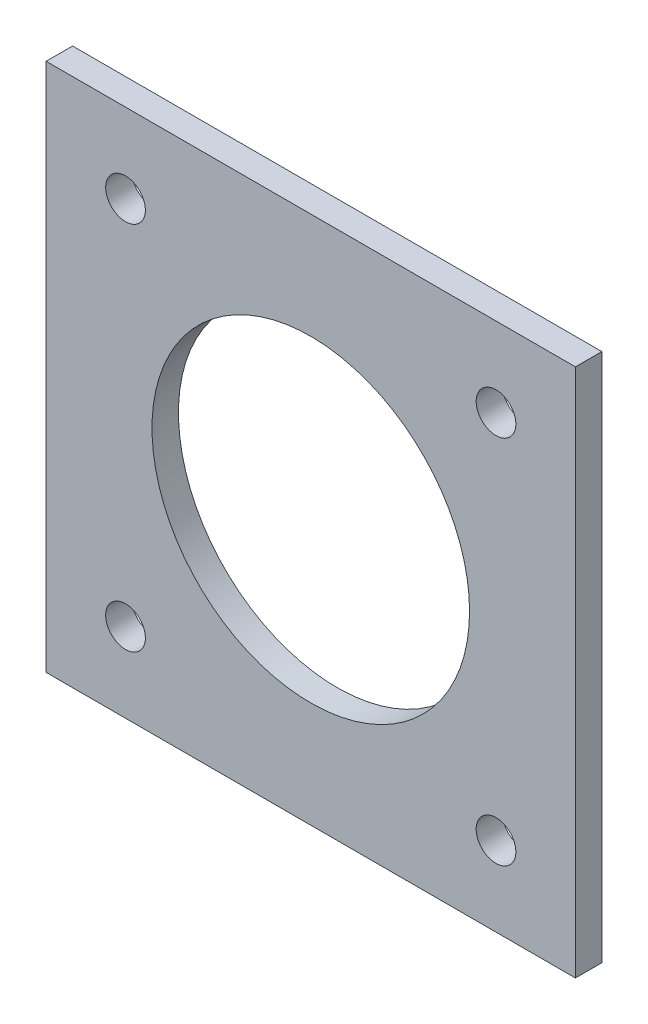
SolidWorks part; units mm, degrees
ref_plane "Plan de face" through (0, 0, 0) normal (0, 0, 1) x (1, 0, 0)
ref_plane "Plan de dessus" through (0, 0, 0) normal (0, 1, 0) x (1, 0, 0)
ref_plane "Plan de droite" through (0, 0, 0) normal (1, 0, 0) x (0, 0, -1)
sketch "Esquisse1" plane through (0, 0, 0) normal (0, 0, 1) x (1, 0, 0)
  line L1 (-16.8433, 28.2256) -> (23.1567, 28.2256)
  line L2 (-16.8433, 28.2256) -> (-16.8433, -11.7744)
  line L3 (-16.8433, -11.7744) -> (23.1567, -11.7744)
  line L4 (23.1567, 28.2256) -> (23.1567, -11.7744)
  circle A0 centre (3.1567, 8.2256) radius 12
  circle A1 centre (-10.8433, 22.2256) radius 1.5
  circle A2 centre (17.1567, 22.2256) radius 1.5
  circle A3 centre (-10.8433, -5.7744) radius 1.5
  circle A4 centre (17.1567, -5.7744) radius 1.5
  dimension "D3" = 20
  dimension "D5" = 6
  dimension "D9" = 6
  dimension "D10" = 6
  dimension "D1" = 40
  dimension "D2" = 40
  dimension "D4" = 20
  dimension "D6" = 6
  dimension "D7" = 6
  dimension "D8" = 6
  dimension "D11" = 6
extrude "Extrusion1" add sketch "Esquisse1" along normal blind 2
